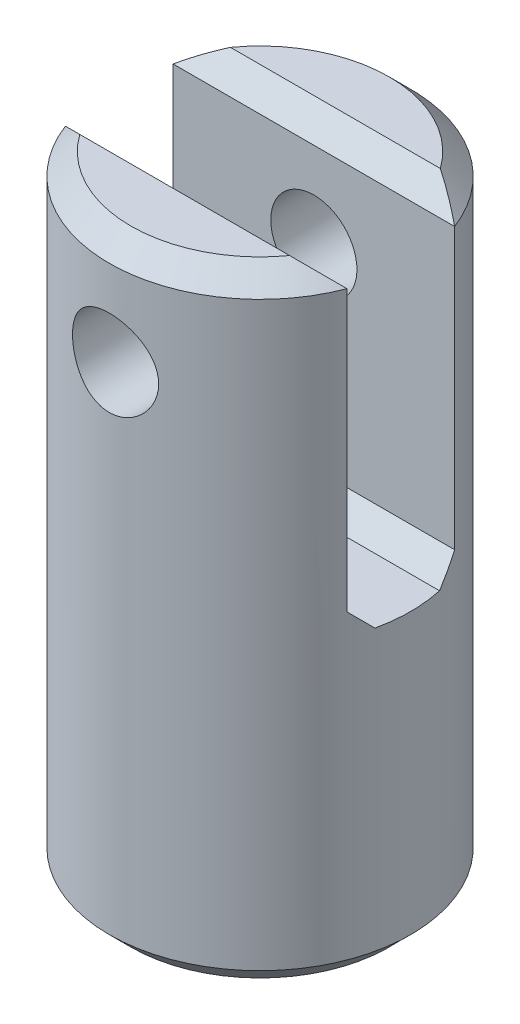
SolidWorks part; units mm, degrees
material "Aço cromo inoxidável"
ref_plane "Plano frontal" through (0, 0, 0) normal (0, 0, 1) x (1, 0, 0)
ref_plane "Plano superior" through (0, 0, 0) normal (0, 1, 0) x (1, 0, 0)
ref_plane "Plano direito" through (0, 0, 0) normal (1, 0, 0) x (0, 0, -1)
sketch "Esboço1" plane through (0, 0, 0) normal (0, 1, 0) x (1, 0, 0)
  circle A0 centre (0, 0) radius 7
  dimension "D1" = 14
extrude "Ressalto-extrusão1" add sketch "Esboço1" along normal mid plane 29
sketch "Esboço2" plane through (0, 0, 0) normal (1, 0, 0) x (0, 0, -1)
  line L0 (7, 14.5) -> (-7, 14.5) construction
  line L1 (-2.5, 14.5) -> (2.5, 14.5)
  line L2 (-2.5, 14.5) -> (-2.5, -0.5)
  line L3 (-2.5, -0.5) -> (2.5, -0.5)
  line L4 (2.5, 14.5) -> (2.5, -0.5)
  line L5 (0, -0.5) -> (0, 14.5) construction
  line L6 (-2.5, 7) -> (2.5, 7) construction
  point P204 (0, 7)
  dimension "D1" = 15
  dimension "D2" = 5
extrude "Corte-extrusão1" cut sketch "Esboço2" against normal through all both and the other way through all
sketch "Esboço3" plane through (0, 0, 0) normal (0, 0, 1) x (1, 0, 0)
  line L0 (0, 14.5) -> (0, 9.5) construction
  line L1 (6.5383, 14.5) -> (-6.5383, 14.5) construction
  circle A0 centre (0, 9.5) radius 2
  dimension "D2" = 4
  dimension "D1" = 5
extrude "Corte-extrusão2" cut sketch "Esboço3" against normal through all both and the other way through all
chamfer "Chanfro1" distance 1 angle 45 1 edges at (0, -14.5, 7)
chamfer "Chanfro2" distance 1 angle 45 6 edges at (0, 14.5, -7) (0, 14.5, -2.5) (0, 14.5, 7) (0, 14.5, 2.5) (0, -0.5, 2.5) (0, -0.5, -2.5)
